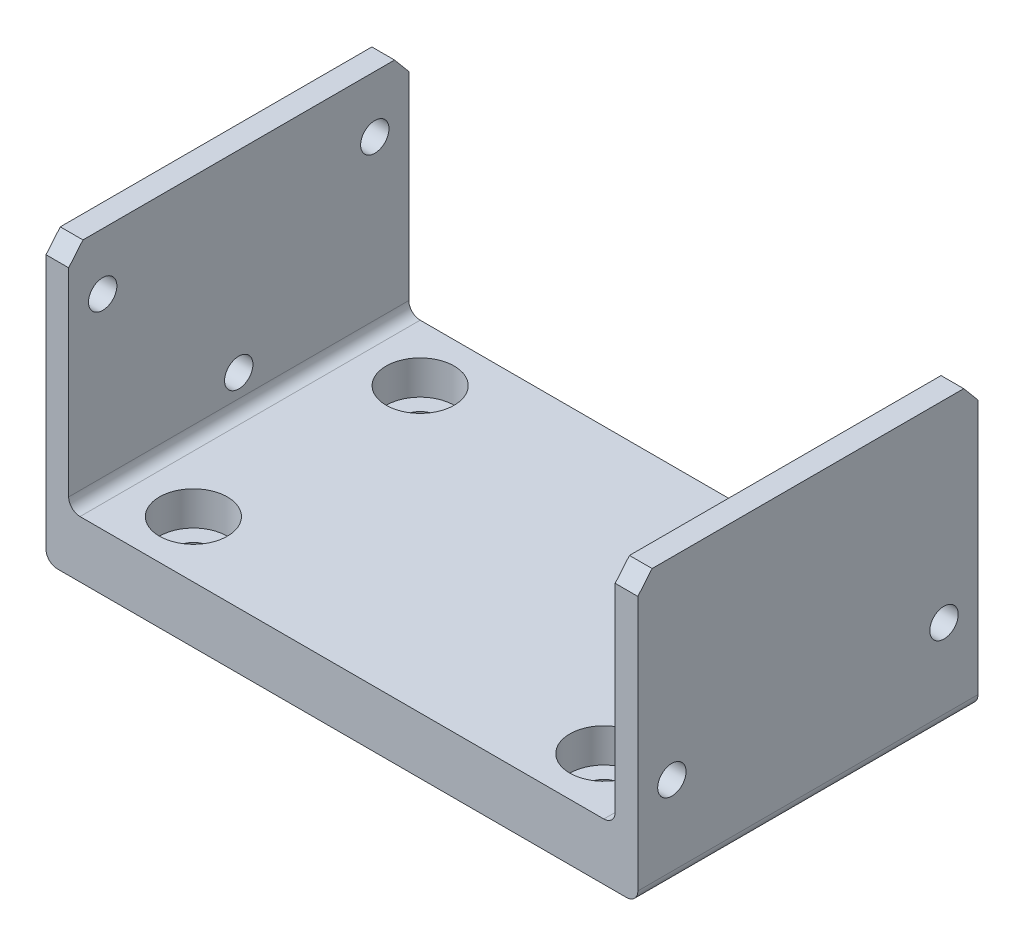
SolidWorks part; units mm, degrees
ref_plane "Front Plane" through (0, 0, 0) normal (0, 0, 1) x (1, 0, 0)
ref_plane "Top Plane" through (0, 0, 0) normal (0, 1, 0) x (1, 0, 0)
ref_plane "Right Plane" through (0, 0, 0) normal (1, 0, 0) x (0, 0, -1)
sketch "Sketch1" plane through (0, 0, 0) normal (0, 1, 0) x (1, 0, 0)
  line L1 (-26.1, -15) -> (26.1, -15)
  line L2 (-26.1, -15) -> (-26.1, 15)
  line L3 (-26.1, 15) -> (26.1, 15)
  line L4 (26.1, -15) -> (26.1, 15)
  point P4 (0, 15)
  point P6 (-26.1, 0)
  dimension "D1" = 52.2
  dimension "D2" = 30
extrude "Boss-Extrude1" add sketch "Sketch1" along normal blind 3
sketch "Sketch2" plane through (0, 3, 0) normal (0, 1, 0) x (1, 0, 0)
  line L0 (26.1, 15) -> (-26.1, 15) construction
  line L1 (-26.1, -15) -> (-24.1, -15)
  line L2 (-26.1, -15) -> (-26.1, 15)
  line L3 (-26.1, 15) -> (-24.1, 15)
  line L4 (-24.1, -15) -> (-24.1, 15)
  dimension "D1" = 2
extrude "Boss-Extrude2" add sketch "Sketch2" along normal blind 20
sketch "Sketch3" plane through (0, 3, 0) normal (0, 1, 0) x (1, 0, 0)
  line L0 (26.1, 15) -> (-24.1, 15) construction
  line L1 (26.1, -15) -> (24.1, -15)
  line L2 (26.1, -15) -> (26.1, 15)
  line L3 (26.1, 15) -> (24.1, 15)
  line L4 (24.1, -15) -> (24.1, 15)
  dimension "D1" = 2
extrude "Boss-Extrude3" add sketch "Sketch3" along normal blind 20
sketch "Sketch4" plane through (26.1, 0, 0) normal (1, 0, 0) x (0, 0, -1)
  circle A0 centre (12, 6) radius 1.2526
  circle A1 centre (-12, 6) radius 1.2502
extrude "Cut-Extrude2" cut sketch "Sketch4" against normal blind 5
sketch "Sketch5" plane through (-24.1, 0, 0) normal (1, 0, 0) x (0, 0, -1)
  circle A0 centre (-12, 18) radius 1.25
  circle A1 centre (12, 18) radius 1.25
  circle A2 centre (0, 6) radius 1.25
extrude "Cut-Extrude4" cut sketch "Sketch5" against normal blind 5
sketch "Sketch6" plane through (0, 3, 0) normal (0, 1, 0) x (1, 0, 0)
  line L1 (-26.1, 15) -> (-26.1, -15) construction
  line L2 (24.1, 15) -> (-24.1, 15) construction
  line L3 (-24.1, -15) -> (24.1, -15) construction
  line L4 (26.1, -15) -> (26.1, 15) construction
  circle A0 centre (-18.1, 10) radius 3
  circle A1 centre (-18.1, -10) radius 3
  circle A2 centre (18.1, 10) radius 3
  circle A3 centre (18.1, -10) radius 3
  point P12 (-16.2183, 10.4512)
  dimension "D1" = 6
  dimension "D2" = 6
  dimension "D3" = 6
  dimension "D4" = 6
  dimension "D5" = 8
  dimension "D6" = 5
  dimension "D7" = 5
  dimension "D8" = 5
  dimension "D9" = 5
  dimension "D10" = 8
  dimension "D11" = 8
  dimension "D12" = 8
extrude "Cut-Extrude5" cut sketch "Sketch6" against normal blind 3
sketch "Sketch7" plane through (0, 0, 0) normal (0, -1, 0) x (1, 0, 0)
  line L1 (-26.1, -15) -> (26.1, -15)
  line L2 (-26.1, -15) -> (-26.1, 15)
  line L3 (-26.1, 15) -> (26.1, 15)
  line L4 (26.1, -15) -> (26.1, 15)
extrude "Boss-Extrude4" add sketch "Sketch7" along normal blind 2
sketch "Sketch8" plane through (0, 0, 0) normal (0, 1, 0) x (1, 0, 0)
  circle A0 centre (-18.1, 10) radius 1.45
  circle A1 centre (18.1, 10) radius 1.45
  circle A2 centre (18.1, -10) radius 1.45
  circle A3 centre (-18.1, -10) radius 1.45
  dimension "D1" = 2.9
  dimension "D2" = 2.9
  dimension "D3" = 2.9
  dimension "D4" = 2.9
extrude "Cut-Extrude6" cut sketch "Sketch8" against normal blind 2
fillet "Fillet1" radius 1 4 edges at (-24.1, 3, 0) (24.1, 3, 0) (26.1, -2, 0) (-26.1, -2, 0)
chamfer "Chamfer2" distance 1.5 angle 40 4 edges at (-25.1, 23, 15) (-25.1, 23, -15) (25.1, 23, -15) (25.1, 23, 15)
